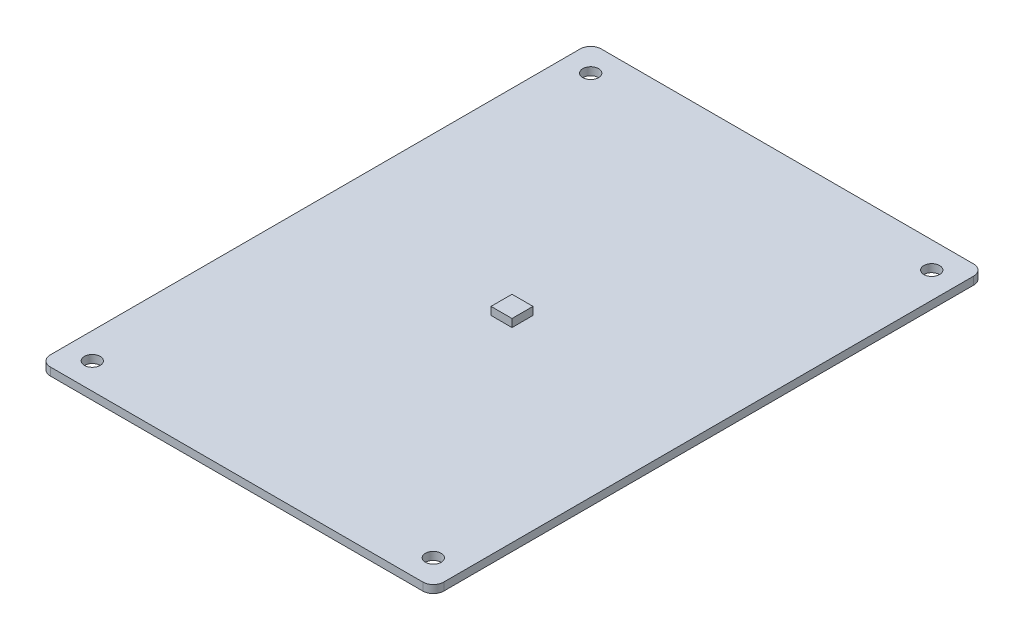
SolidWorks part; units mm, degrees
ref_plane "Plan de face" through (0, 0, 0) normal (0, 0, 1) x (1, 0, 0)
ref_plane "Plan de dessus" through (0, 0, 0) normal (0, 1, 0) x (1, 0, 0)
ref_plane "Plan de droite" through (0, 0, 0) normal (1, 0, 0) x (0, 0, -1)
sketch "Esquisse1" plane through (0, 0, 0) normal (0, 1, 0) x (1, 0, 0)
  line L0 (43.5142, -17.0401) -> (38.5142, -17.0401) construction
  line L1 (-29.4858, 82.9599) -> (41.5142, 82.9599)
  line L2 (-31.4858, 80.9599) -> (-31.4858, -20.0401)
  line L3 (-29.4858, -22.0401) -> (41.5142, -22.0401)
  line L4 (43.5142, 80.9599) -> (43.5142, -20.0401)
  line L5 (38.5142, -17.0401) -> (38.5142, -22.0401) construction
  line L6 (43.5142, 77.9599) -> (38.5142, 77.9599) construction
  line L7 (38.5142, 77.9599) -> (38.5142, 82.9599) construction
  line L8 (38.5142, 82.9599) -> (-26.4858, 82.9599) construction
  line L9 (-26.4858, 82.9599) -> (-26.4858, 77.9599) construction
  line L10 (-26.4858, 77.9599) -> (-31.4858, 77.9599) construction
  line L11 (-31.4858, 77.9599) -> (-31.4858, -17.0401) construction
  line L12 (-31.4858, -17.0401) -> (-26.4858, -17.0401) construction
  line L13 (-26.4858, -17.0401) -> (-26.4858, -22.0401) construction
  circle A0 centre (38.5142, 77.9599) radius 1.5
  circle A1 centre (38.5142, -17.0401) radius 1.5
  circle A2 centre (-26.4858, -17.0401) radius 1.5
  circle A3 centre (-26.4858, 77.9599) radius 1.5
  arc A4 (41.5142, -22.0401) -> (43.5142, -20.0401) centre (41.5142, -20.0401) ccw
  arc A5 (-31.4858, -20.0401) -> (-29.4858, -22.0401) centre (-29.4858, -20.0401) ccw
  arc A6 (-29.4858, 82.9599) -> (-31.4858, 80.9599) centre (-29.4858, 80.9599) ccw
  arc A7 (41.5142, 82.9599) -> (43.5142, 80.9599) centre (41.5142, 80.9599) cw
  point P22 (43.5142, -22.0401)
  point P27 (-31.4858, 82.9599)
  point P30 (43.5142, 82.9599)
  dimension "D3" = 2
  dimension "D1" = 75
  dimension "D2" = 105
extrude "Boss.-Extru.1" add sketch "Esquisse1" along normal blind 1.5
sketch "Esquisse2" plane through (0, 1.5, 0) normal (0, 1, 0) x (1, 0, 0)
  line L0 (-31.4858, -22.0401) -> (43.5142, 82.9599) construction
  line L1 (-31.4858, 82.9599) -> (43.5142, -22.0401) construction
  line L3 (4.0142, 28.4599) -> (8.0142, 28.4599)
  line L4 (4.0142, 28.4599) -> (4.0142, 32.4599)
  line L5 (4.0142, 32.4599) -> (8.0142, 32.4599)
  line L6 (8.0142, 28.4599) -> (8.0142, 32.4599)
  line L7 (4.0142, 28.4599) -> (8.0142, 32.4599) construction
  line L8 (4.0142, 32.4599) -> (8.0142, 28.4599) construction
  point P8 (6.0142, 30.4599)
  dimension "D1" = 4
  dimension "D2" = 4
extrude "Boss.-Extru.2" add sketch "Esquisse2" along normal blind 1.5
